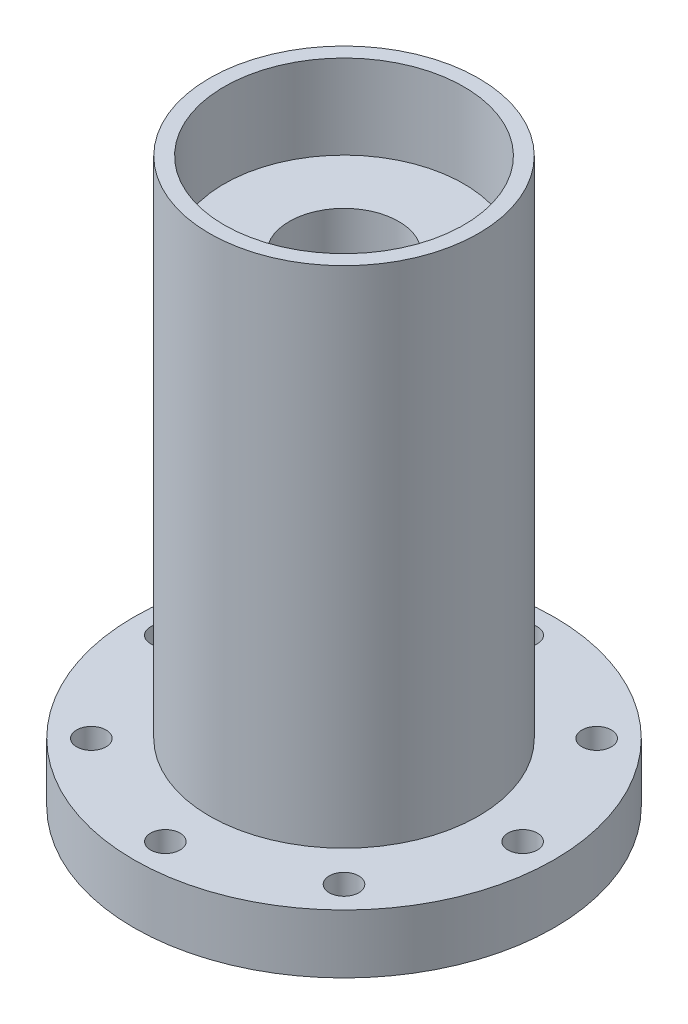
SolidWorks part; units mm, degrees
ref_plane "Front Plane" through (0, 0, 0) normal (0, 0, 1) x (1, 0, 0)
ref_plane "Top Plane" through (0, 0, 0) normal (0, 1, 0) x (1, 0, 0)
ref_plane "Right Plane" through (0, 0, 0) normal (1, 0, 0) x (0, 0, -1)
sketch "Sketch1" plane through (0, 0, 0) normal (1, 0, 0) x (0, 0, -1)
  line L0 (0, 150) -> (0, -163.75) construction
  line L1 (-16, -48.0966) -> (-16, -108.0966)
  line L2 (-16, -108.0966) -> (-25, -108.0966)
  line L4 (-25, -115.0966) -> (-14.25, -115.0966)
  line L8 (-14.25, -48.0966) -> (-16, -48.0966)
  line L10 (-14.25, -48.0966) -> (-14.25, -58.0966)
  line L12 (-14.25, -58.0966) -> (-6.5, -58.0966)
  line L13 (-6.5, -58.0966) -> (-6.5, -105.0966)
  line L17 (-25, -108.0966) -> (-25, -115.0966) construction
  line L18 (-25, -115.0966) -> (-25, -108.0966)
  line L19 (-5.25, -48.0966) -> (-5.25, -115.7911) construction
  line L20 (5.25, -48.0966) -> (5.25, -115.7911) construction
  line L21 (-14.25, -115.0966) -> (-14.25, -105.0966)
  line L22 (-14.25, -105.0966) -> (-6.5, -105.0966)
  dimension "D1" = 13
  dimension "D2" = 50
  dimension "D3" = 60
  dimension "D4" = 32
  dimension "D5" = 10.5
  dimension "D6" = 10
  dimension "D7" = 7
  dimension "D9" = 10
  dimension "D10" = 28.5
  dimension "D8" = 57
  dimension "28,5" = 28.5
revolve "Revolve1" add sketch "Sketch1" angle 360 about L0
sketch "Sketch3" plane through (0, -115.0966, 0) normal (0, -1, 0) x (1, 0, 0)
  line L0 (0, 0) -> (-15.026, 15.026) construction
  line L1 (0, -30.1398) -> (0, 30.0638) construction
  line L2 (-15.026, -15.026) -> (0, 0) construction
  circle A0 centre (0, 0) radius 21.25 construction
  circle A1 centre (0, 0) radius 25
  circle A10 centre (0, -21.25) radius 1.75
  circle A11 centre (-15.026, -15.026) radius 1.75
  circle A12 centre (-21.25, 0) radius 1.75
  circle A13 centre (-15.026, 15.026) radius 1.75
  circle A14 centre (0, 21.25) radius 1.75
  circle A15 centre (15.026, 15.026) radius 1.75
  circle A16 centre (21.25, 0) radius 1.75
  circle A17 centre (15.026, -15.026) radius 1.75
  circle A19 centre (0, 0) radius 25
  dimension "D2" = 42.5
  dimension "D3" = 3.5
  dimension "D4" = 45
  dimension "D5" = 90
  dimension "D1" = 0
extrude "Cut-Extrude1" cut sketch "Sketch3" against normal blind 10 contours A13 | A14 | A15 | A12 | A16 | A11 | A10 | A17
sketch "Sketch4" plane through (0, -115.0966, 0) normal (0, -1, 0) x (1, 0, 0)
  circle A0 centre (0, 0) radius 14.25 construction
  circle A1 centre (0, 21.25) radius 1.75
  circle A2 centre (0, 21.25) radius 1.75 construction
  circle A3 centre (-15.026, 15.026) radius 1.75
  circle A4 centre (-15.026, 15.026) radius 1.75 construction
  circle A5 centre (15.026, 15.026) radius 1.75
  circle A6 centre (15.026, 15.026) radius 1.75 construction
  circle A7 centre (-21.25, 0) radius 1.75
  circle A8 centre (-21.25, 0) radius 1.75 construction
  circle A9 centre (21.25, 0) radius 1.75
  circle A10 centre (21.25, 0) radius 1.75 construction
  circle A11 centre (-15.026, -15.026) radius 1.75
  circle A12 centre (-15.026, -15.026) radius 1.75 construction
  circle A13 centre (0, -21.25) radius 1.75
  circle A14 centre (0, -21.25) radius 1.75 construction
  circle A15 centre (15.026, -15.026) radius 1.75
  circle A16 centre (15.026, -15.026) radius 1.75 construction
  circle A17 centre (0, 0) radius 14.25 construction
  circle A18 centre (0, 0) radius 25 construction
  circle A19 centre (0, 0) radius 25 construction
  dimension "D1" = 0
  dimension "D2" = 0
  dimension "D3" = 0
  dimension "D4" = 0
  dimension "D5" = 0
  dimension "D6" = 0
  dimension "D7" = 0
  dimension "D8" = 0
